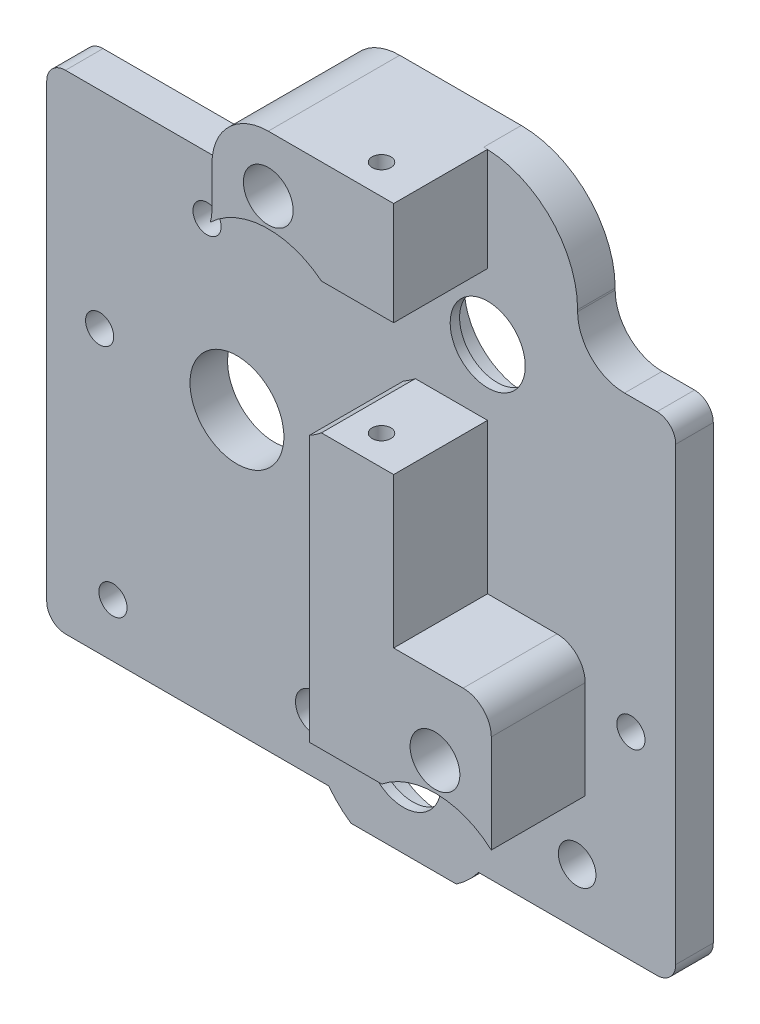
SolidWorks part; units mm, degrees
ref_plane "Plano frontal" through (0, 0, 0) normal (0, 0, 1) x (1, 0, 0)
ref_plane "Plano superior" through (0, 0, 0) normal (0, 1, 0) x (1, 0, 0)
ref_plane "Plano direito" through (0, 0, 0) normal (1, 0, 0) x (0, 0, -1)
sketch "Esboço1" plane through (0, 0, 0) normal (0, 0, 1) x (1, 0, 0)
  line L0 (28.0486, 26) -> (31.5, 26)
  line L1 (-31.5, -26) -> (-3.46, -26)
  line L2 (-33.5, -24) -> (-33.5, 24)
  line L3 (-31.5, 26) -> (-10.901, 26)
  line L4 (33.5, -24) -> (33.5, 24)
  line L5 (-33.5, -26) -> (33.5, 26) construction
  line L6 (-33.5, 26) -> (33.5, -26) construction
  line L7 (12.5, -26) -> (31.5, -26)
  line L8 (-5.901, 35.1814) -> (-5.901, 31)
  line L9 (23.0486, 31) -> (23.0486, 31.1814)
  line L10 (2.52, 26) -> (-33.48, 26) construction
  line L11 (13.0486, 41.1814) -> (0.099, 41.1814)
  line L12 (-1.0941, -28.256) -> (10.1341, -28.256)
  arc A0 (-3.46, -26) -> (-1.0941, -28.256) centre (4.52, -20) ccw
  circle A1 centre (0.099, 35.1814) radius 2.5
  arc A2 (23.0486, 31.1814) -> (13.0486, 41.1814) centre (13.0486, 31.1814) ccw
  arc A3 (0.099, 41.1814) -> (-5.901, 35.1814) centre (0.099, 35.1814) ccw
  arc A4 (-5.901, 31) -> (-10.901, 26) centre (-10.901, 31) cw
  arc A5 (23.0486, 31) -> (28.0486, 26) centre (28.0486, 31) ccw
  circle A6 centre (17.855, -8) radius 2.5
  arc A7 (-31.5, -26) -> (-33.5, -24) centre (-31.5, -24) cw
  arc A8 (31.5, -26) -> (33.5, -24) centre (31.5, -24) ccw
  arc A9 (31.5, 26) -> (33.5, 24) centre (31.5, 24) cw
  arc A10 (-33.5, 24) -> (-31.5, 26) centre (-31.5, 24) cw
  arc A11 (10.1341, -28.256) -> (12.5, -26) centre (4.52, -20) ccw
  point P0 (0, 0)
  point P26 (-5.901, 26)
  point P28 (23.0486, 26)
  dimension "D1" = 12
  dimension "D2" = 5
  dimension "D3" = 10
  dimension "D4" = 5
  dimension "D5" = 12
  dimension "D6" = 2
extrude "Ressalto-extrusão1" add sketch "Esboço1" along normal blind 4
sketch "Esboço2" plane through (0, 0, 0) normal (0, 0, -1) x (-1, 0, 0)
  circle A0 centre (-28.7284, -4.9206) radius 1.5
  circle A1 centre (16.4233, 19.8536) radius 1.5
  circle A2 centre (27.863, 3.9864) radius 1.5
  circle A3 centre (26.4471, -20.3191) radius 1.5
  circle A4 centre (13.2389, 3.8057) radius 5
  circle A5 centre (-13.474, 23.1814) radius 4
  circle A6 centre (-4.5, -20) radius 4
  circle A7 centre (-23, -20) radius 2
  circle A8 centre (5, -20) radius 2
extrude "Corte-extrusão1" cut sketch "Esboço2" against normal blind 4
sketch "Esboço3" plane through (0, 0, 0) normal (0, 0, -1) x (-1, 0, 0)
  circle A0 centre (-13.474, 23.1814) radius 6.5
  circle A1 centre (-4.5, -20) radius 6.5
extrude "Cut-Extrude1" cut sketch "Esboço3" against normal blind 3
sketch "Sketch1" plane through (0, 0, 4) normal (0, 0, 1) x (1, 0, 0)
  line L0 (13.454, 16.1814) -> (13.454, 0.1814)
  line L1 (13.454, 0.1814) -> (20.855, 0.1814)
  line L2 (23.855, -2.8186) -> (23.855, -13.2571)
  line L3 (4.5, -13) -> (4.5, 15.3309)
  line L6 (13.454, 41.1814) -> (0.099, 41.1814)
  line L7 (-5.901, 35.1814) -> (-5.901, 31)
  line L8 (13.454, 30.1836) -> (13.454, 41.1814)
  line L9 (13.454, 16.1814) -> (5.7603, 16.1814)
  line L10 (4.5, -13) -> (12.1981, -13)
  line L11 (13.454, 30.1836) -> (5.7576, 30.1836)
  arc A0 (23.855, -13.2571) -> (12.1981, -13) centre (17.875, -20) ccw
  arc A1 (20.855, 0.1814) -> (23.855, -2.8186) centre (20.855, -2.8186) cw
  arc A3 (5.7576, 30.1836) -> (-6.0732, 29.6992) centre (0.119, 23.1814) ccw
  circle A4 centre (17.855, -8) radius 2.5 construction
  circle A5 centre (17.855, -8) radius 2.5
  circle A6 centre (0.099, 35.1814) radius 2.5
  arc A10 (0.099, 41.1814) -> (-5.901, 35.1814) centre (0.099, 35.1814) ccw
  arc A11 (-6.0732, 29.6992) -> (-5.901, 31) centre (-10.901, 31) ccw
  arc A13 (4.5, 15.3309) -> (5.7603, 16.1814) centre (0.119, 23.1814) ccw
  dimension "D1" = 6
  dimension "D2" = 3
extrude "Boss-Extrude1" add sketch "Sketch1" along normal blind 10
sketch "Sketch2" plane through (0, 41.1814, 0) normal (0, 1, 0) x (-1, 0, 0)
  circle A0 centre (-8.9939, 10.8323) radius 1
extrude "Cut-Extrude3" cut sketch "Sketch2" against normal blind 58
hole_wizard "CSK for M5 Flat Head Machine Screw1" positions "Sketch6" profile "Sketch5" countersink size "M5" standard "Ansi Metric" end condition through all
sketch "Sketch6" plane through (0, 0, 0) normal (0, 0, -1) x (-1, 0, 0)
  point P1 (-0.099, 35.1814)
  point P4 (-17.855, -8)
sketch "Sketch5" plane through (0.099, 35.1814, 0) normal (1, 0, 0) x (0, 1, 0)
  line L0 (0, 0) -> (0, 14)
  line L1 (0, 14) -> (2.65, 14)
  line L2 (2.65, 14) -> (2.65, 2.55)
  line L3 (2.65, 2.55) -> (5.2, 0)
  line L5 (5.2, 0) -> (0, 0)
  line L6 (-2.65, 2.55) -> (-5.2, 0) construction
  line L11 (0, -6.35) -> (0, 107.95) construction
  dimension "Thru Hole Dia." = 5.3
  dimension "Thru Hole Depth" = 14
  dimension "Near C'Sink Dia." = 10.4
  dimension "Near C'Sink Angle" = 90
